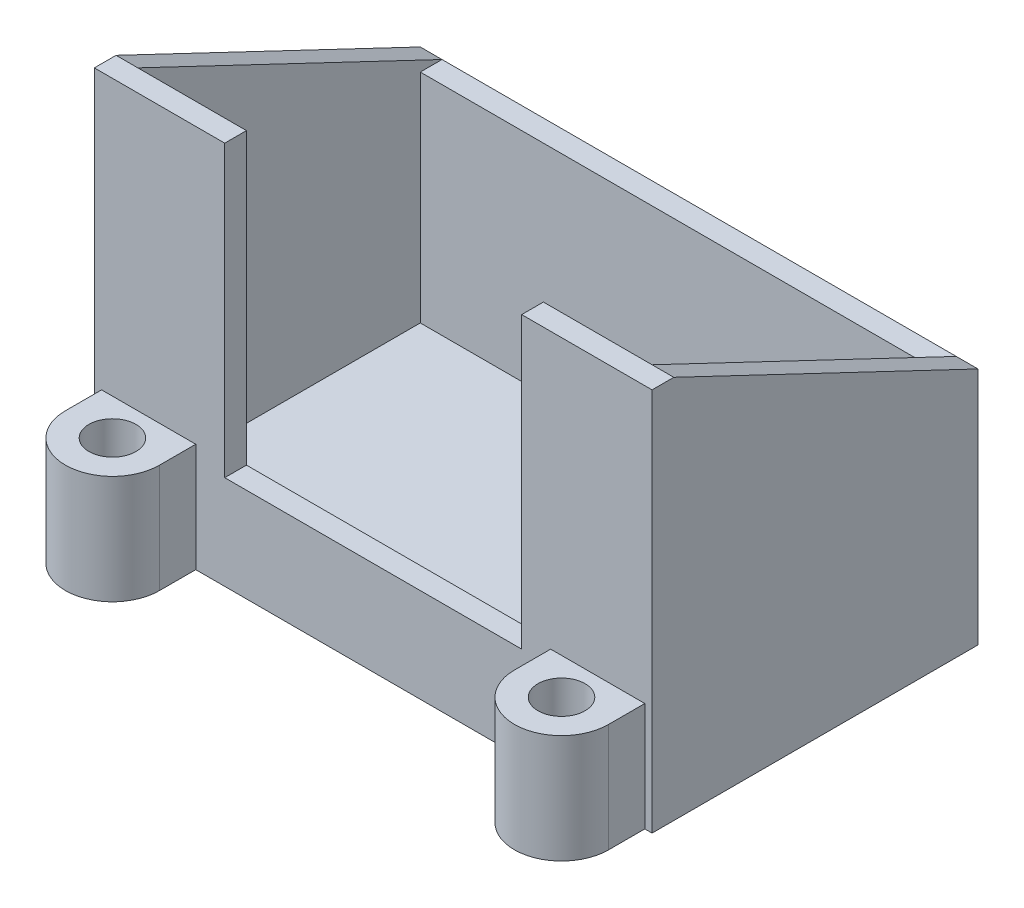
SolidWorks part; units mm, degrees
ref_plane "前视基准面" through (0, 0, 0) normal (0, 0, 1) x (1, 0, 0)
ref_plane "上视基准面" through (0, 0, 0) normal (0, 1, 0) x (1, 0, 0)
ref_plane "右视基准面" through (0, 0, 0) normal (1, 0, 0) x (0, 0, -1)
sketch "草图1" plane through (0, 0, 0) normal (0, 1, 0) x (1, 0, 0)
  line L1 (38.5, -22.5) -> (-38.5, -22.5)
  line L2 (38.5, -22.5) -> (38.5, 22.5)
  line L3 (38.5, 22.5) -> (-38.5, 22.5)
  line L4 (-38.5, -22.5) -> (-38.5, 22.5)
  line L5 (0, 22.5) -> (0, -22.5) construction
  line L6 (38.5, 0) -> (-38.5, 0) construction
  point P0 (0, 0)
  dimension "D1" = 77
  dimension "D2" = 45
extrude "凸台-拉伸1" add sketch "草图1" along normal blind 33
sketch "草图2" plane through (0, 33, 0) normal (0, 1, 0) x (1, 0, 0)
  line L0 (-38.5, -22.5) -> (38.5, -22.5) construction
  line L2 (35.5, -19.5) -> (35.5, 19.5)
  line L3 (35.5, 19.5) -> (-35.5, 19.5)
  line L4 (-35.5, -19.5) -> (-35.5, 19.5)
  line L5 (0, 19.5) -> (0, -18.5) construction
  line L6 (35.5, 0) -> (-35.5, 0) construction
  line L8 (-20.5, -19.5) -> (-20.5, -22.5)
  line L9 (-20.5, -22.5) -> (20.5, -22.5)
  line L10 (20.5, -19.5) -> (20.5, -22.5)
  line L11 (-38.5, 22.5) -> (-38.5, -22.5) construction
  line L12 (38.5, -22.5) -> (38.5, 22.5) construction
  line L13 (-35.5, -19.5) -> (-20.5, -19.5)
  line L14 (20.5, -19.5) -> (35.5, -19.5)
  point P0 (0, 0)
  point P12 (-20.5, -21)
  dimension "D1" = 71
  dimension "D2" = 39
  dimension "D3" = 18
  dimension "D4" = 18
extrude "切除-拉伸1" cut sketch "草图2" against normal blind 30
sketch "草图5" plane through (0, 33, 0) normal (0, 1, 0) x (1, 0, 0)
  line L1 (-20.5, -19.5) -> (-38.5, -19.5)
  line L2 (-20.5, -19.5) -> (-20.5, -22.5)
  line L3 (-20.5, -22.5) -> (-38.5, -22.5)
  line L4 (-38.5, -19.5) -> (-38.5, -22.5)
  line L5 (20.5, -19.5) -> (38.5, -19.5)
  line L6 (20.5, -19.5) -> (20.5, -22.5)
  line L7 (20.5, -22.5) -> (38.5, -22.5)
  line L8 (38.5, -19.5) -> (38.5, -22.5)
extrude "凸台-拉伸3" add sketch "草图5" along normal blind 20
sketch "草图7" plane through (38.5, 0, 0) normal (1, 0, 0) x (0, 0, -1)
  line L0 (22.5, 33) -> (-19.5, 33)
  line L1 (-19.5, 33) -> (-19.5, 53)
  line L2 (-19.5, 53) -> (-19.5, 33) construction
  line L3 (-19.5, 53) -> (22.5, 33)
  dimension "D1" = 20
extrude "凸台-拉伸4" add sketch "草图7" against normal blind 3
mirror "镜向1" about plane through (0, 0, 0) normal (1, 0, 0) of "凸台-拉伸4"
sketch "草图8" plane through (0, 3, 0) normal (0, 1, 0) x (1, 0, 0)
  line L1 (-20.5, -19.5) -> (20.5, -19.5)
  line L2 (-20.5, -19.5) -> (-20.5, -22.5)
  line L3 (-20.5, -22.5) -> (20.5, -22.5)
  line L4 (20.5, -19.5) -> (20.5, -22.5)
extrude "凸台-拉伸6" add sketch "草图8" along normal blind 10
sketch "草图4" plane through (0, 0, 0) normal (0, 1, 0) x (1, 0, 0)
  line L0 (-38.5, -22.5) -> (38.5, -22.5) construction
  line L10 (-37.5, -27.5) -> (-37.5, -22.5)
  line L11 (-24.5, -27.5) -> (-24.5, -22.5)
  line L12 (-24.5, -22.5) -> (-37.5, -22.5)
  line L13 (37.5, -27.5) -> (37.5, -22.5)
  line L14 (37.5, -22.5) -> (24.5, -22.5)
  line L15 (24.5, -22.5) -> (24.5, -27.5)
  circle A0 centre (-31, -27.5) radius 3.25
  circle A1 centre (31, -27.5) radius 3.25
  arc A2 (-24.5, -27.5) -> (-37.5, -27.5) centre (-31, -27.5) cw
  arc A3 (24.5, -27.5) -> (37.5, -27.5) centre (31, -27.5) ccw
  dimension "D2" = 5
  dimension "D3" = 5
  dimension "D4" = 6.5
  dimension "D5" = 6.5
  dimension "D6" = 6.5
  dimension "D7" = 6.5
  dimension "D1" = 31
  dimension "21" = 31
extrude "凸台-拉伸2" add sketch "草图4" along normal blind 15
